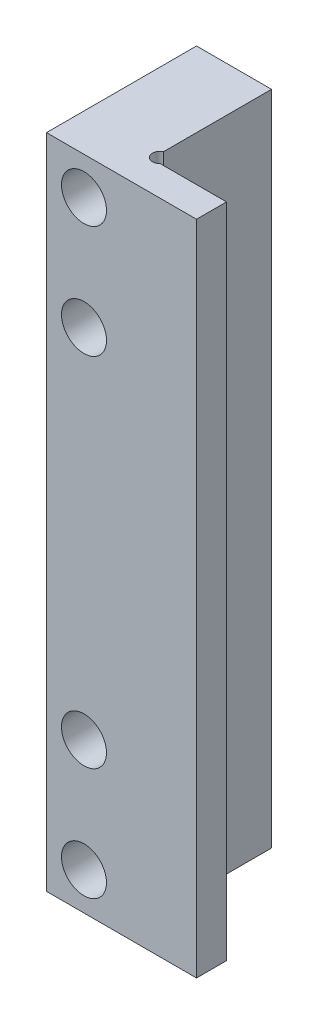
SolidWorks part; units mm, degrees
ref_plane "前基準面" through (0, 0, 0) normal (0, 0, 1) x (1, 0, 0)
ref_plane "上基準面" through (0, 0, 0) normal (0, 1, 0) x (1, 0, 0)
ref_plane "右基準面" through (0, 0, 0) normal (1, 0, 0) x (0, 0, -1)
sketch "草圖1" plane through (0, 0, 0) normal (0, 0, 1) x (1, 0, 0)
  line L0 (-29.9, 26.9) -> (-29.9, -26.9) construction
  line L1 (-38, 30) -> (38, 30) construction
  line L2 (-38, 30) -> (-38, -30) construction
  line L3 (-38, -30) -> (38, -30) construction
  line L4 (38, 30) -> (38, -30) construction
  line L5 (-38, 30) -> (38, -30) construction
  line L6 (-38, -30) -> (38, 30) construction
  line L7 (-29.9, 26.9) -> (29.9, 26.9) construction
  line L8 (-34.9, 21.9) -> (-34.9, -21.9) construction
  line L9 (-29.9, -26.9) -> (29.9, -26.9) construction
  line L10 (34.9, 21.9) -> (34.9, -21.9) construction
  line L11 (-34.9, 26.9) -> (34.9, -26.9) construction
  line L12 (-34.9, -26.9) -> (34.9, 26.9) construction
  line L13 (-34.9, 21.9) -> (-24.9, 21.9)
  line L14 (-24.9, 21.9) -> (-24.9, -21.9)
  line L15 (-24.9, -21.9) -> (-34.9, -21.9)
  line L16 (-34.9, 21.9) -> (-34.9, -21.9)
  arc A0 (29.9, -26.9) -> (34.9, -21.9) centre (29.9, -21.9) ccw construction
  arc A1 (29.9, 26.9) -> (34.9, 21.9) centre (29.9, 21.9) cw construction
  arc A2 (-34.9, -21.9) -> (-29.9, -26.9) centre (-29.9, -21.9) ccw construction
  arc A3 (-29.9, 26.9) -> (-34.9, 21.9) centre (-29.9, 21.9) ccw construction
  point P0 (0, 0)
  point P6 (0, 0)
  dimension "D5" = 5
  dimension "D1" = 76
  dimension "D2" = 60
  dimension "D3" = 3.1
  dimension "D4" = 3.1
  dimension "D6" = 5
  dimension "D7" = 10
extrude "填料-伸長1" add sketch "草圖1" against normal blind 10
sketch "草圖2" plane through (0, -21.9, 0) normal (0, -1, 0) x (1, 0, 0)
  line L0 (-24.9, -10) -> (-24.9, -2)
  line L1 (-24.9, -10) -> (-24.9, 0) construction
  line L2 (-24.9, -2) -> (-29.9, -2)
  line L3 (-29.9, -2) -> (-29.9, -10)
  line L4 (-34.9, -10) -> (-24.9, -10) construction
  line L5 (-29.9, -10) -> (-24.9, -10)
  line L6 (-27.4, -2) -> (-27.4, -10) construction
  line L7 (-29.9, -6) -> (-24.9, -6) construction
  line L8 (-27.4, -6) -> (-29.9, -2) construction
  circle A0 centre (-29.684, -2.3456) radius 0.5
  dimension "D3" = 1
  dimension "D4" = 0.3456
  dimension "D1" = 8
  dimension "D2" = 5
extrude "除料-伸長1" cut sketch "草圖2" against normal through all
sketch "草圖3" plane through (0, 0, 0) normal (0, 0, 1) x (1, 0, 0)
  line L0 (-34.9, 21.9) -> (-34.9, -21.9) construction
  line L1 (-24.9, 21.9) -> (-34.9, 21.9) construction
  line L2 (0, 0) -> (-34.9, 0) construction
  circle A0 centre (-32.4, 19.4) radius 1.5
  circle A1 centre (-32.4, -19.4) radius 1.5
  dimension "D1" = 3
  dimension "D2" = 2.5
  dimension "D3" = 2.5
extrude "除料-伸長2" cut sketch "草圖3" against normal through all
sketch "草圖4" plane through (0, 0, 0) normal (0, 0, 1) x (1, 0, 0)
  line L0 (-34.9, 21.9) -> (-34.9, -21.9) construction
  line L1 (-24.9, 21.9) -> (-34.9, 21.9) construction
  line L2 (-34.9, 0) -> (-24.9, 0) construction
  line L3 (-24.9, -21.9) -> (-24.9, 21.9) construction
  circle A0 centre (-32.4, 11.9) radius 1.5
  circle A1 centre (-32.4, -11.9) radius 1.5
  dimension "D1" = 2.5
  dimension "D3" = 3
  dimension "D2" = 10
extrude "除料-伸長3" cut sketch "草圖4" against normal blind 5
